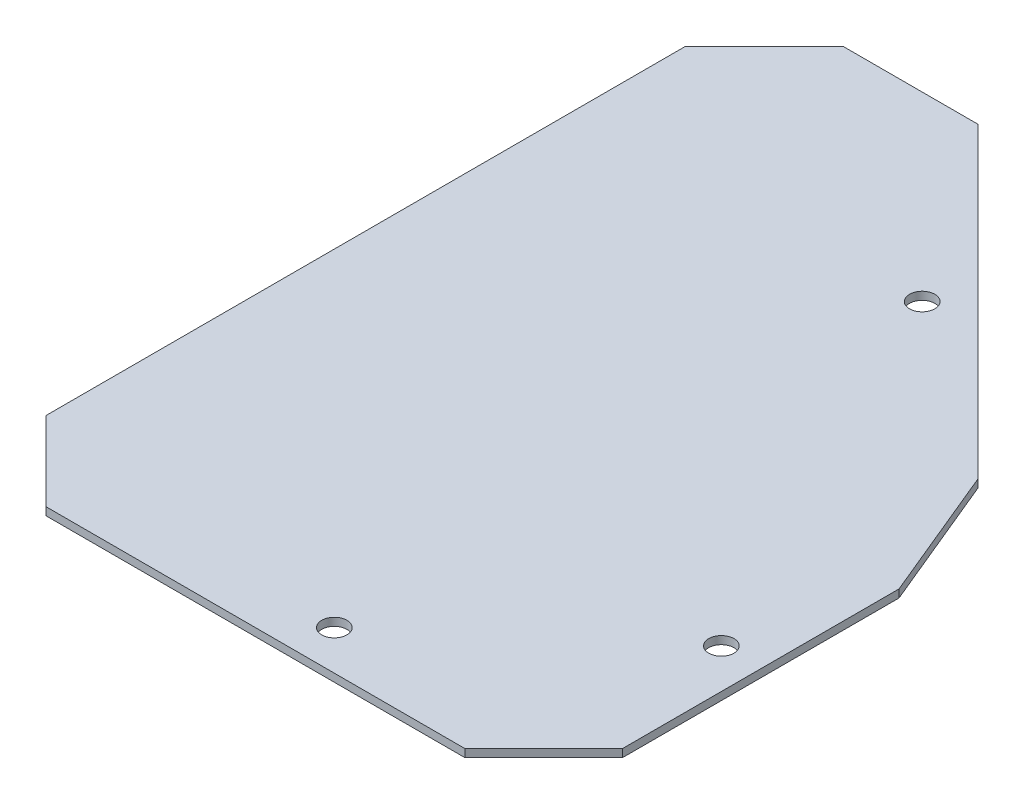
SolidWorks part; units mm, degrees
ref_plane "前视基准面" through (0, 0, 0) normal (0, 0, 1) x (1, 0, 0)
ref_plane "上视基准面" through (0, 0, 0) normal (0, 1, 0) x (1, 0, 0)
ref_plane "右视基准面" through (0, 0, 0) normal (1, 0, 0) x (0, 0, -1)
other "Configuration Table"
sketch "草图1" plane through (0, 0, 0) normal (0, 1, 0) x (1, 0, 0)
  line L0 (0, 0) -> (53.033, 0)
  line L1 (53.033, 0) -> (53.033, 55)
  line L2 (53.033, 55) -> (0, 108.033)
  line L3 (0, 108.033) -> (0, 0)
  dimension "D1" = 45
  dimension "D2" = 75
  dimension "D3" = 55
extrude "凸台-拉伸1" add sketch "草图1" along normal blind 1
chamfer "倒角1" distance 10 angle 45 2 edges at (0, 0.5, -108.033) (53.033, 0.5, 0)
chamfer "倒角2" distance 10 1 edges at (53.033, 0.5, -55)
sketch "草图3" plane through (0, 0, 0) normal (0, -1, 0) x (1, 0, 0)
  line L0 (22.981, -77.981) -> (26.5165, -81.5165) construction
  line L1 (45.9619, -62.0711) -> (7.0711, -100.9619) construction
  line L2 (48.033, -27.5) -> (53.033, -27.5) construction
  line L3 (53.033, -10) -> (53.033, -45) construction
  line L4 (21.5165, -5) -> (21.5165, 0) construction
  line L5 (0, 0) -> (43.033, 0) construction
  circle A0 centre (22.981, -77.981) radius 1.6
  circle A1 centre (48.033, -27.5) radius 1.6
  circle A2 centre (21.5165, -5) radius 1.6
  dimension "D1" = 5
  dimension "D2" = 3.2
  dimension "D3" = 3.2
  dimension "D6" = 3.2
  dimension "D4" = 5
  dimension "D5" = 5
extrude "切除-拉伸2" cut sketch "草图3" against normal blind 10
sketch "草图4" plane through (0, 0, 0) normal (0, -1, 0) x (1, 0, 0)
  line L0 (0, -100.9619) -> (7.0711, -100.9619) construction
  line L1 (0, 0) -> (-20, 0)
  line L2 (0, 0) -> (0, -100.9619)
  line L3 (0, -100.9619) -> (-20, -100.9619)
  line L4 (-20, 0) -> (-20, -100.9619)
  line L5 (0, -100.9619) -> (0, 0) construction
  dimension "D1" = 20
extrude "凸台-拉伸2" add sketch "草图4" against normal up to surface (1 mm away) up to face at (22.981, 1, -76.381)
chamfer "倒角3" distance 10 angle 45 2 edges at (-20, 0.5, 0) (-20, 0.5, -100.9619)
